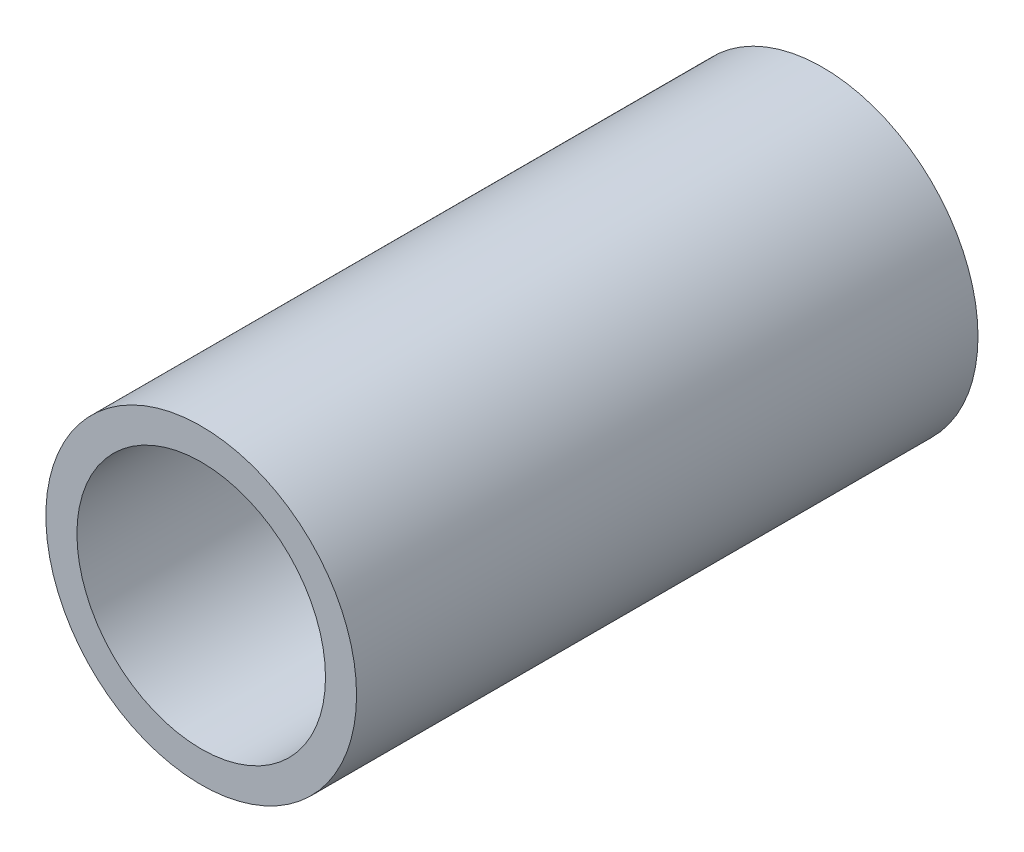
SolidWorks part; units mm, degrees
ref_plane "Plano frontal" through (0, 0, 0) normal (0, 0, 1) x (1, 0, 0)
ref_plane "Plano superior" through (0, 0, 0) normal (0, 1, 0) x (1, 0, 0)
ref_plane "Plano direito" through (0, 0, 0) normal (1, 0, 0) x (0, 0, -1)
sketch "Esboço1" plane through (0, 0, 0) normal (0, 0, 1) x (1, 0, 0)
  circle A0 centre (0, 0) radius 12.5
  circle A1 centre (0, 0) radius 10
  dimension "D1" = 25
  dimension "D2" = 20
extrude "Ressalto-extrusão1" add sketch "Esboço1" along normal blind 50
